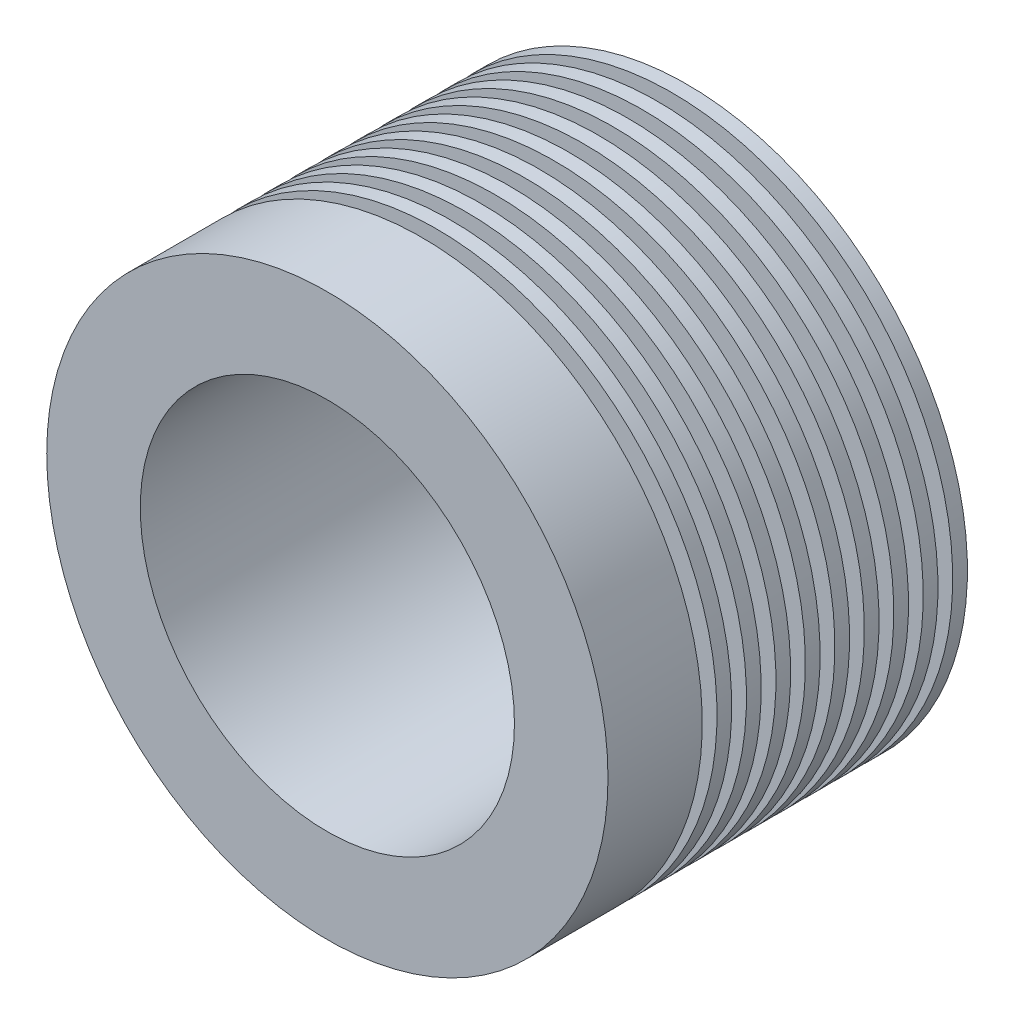
SolidWorks part; units mm, degrees
ref_plane "Plan de face" through (0, 0, 0) normal (0, 0, 1) x (1, 0, 0)
ref_plane "Plan de dessus" through (0, 0, 0) normal (0, 1, 0) x (1, 0, 0)
ref_plane "Plan de droite" through (0, 0, 0) normal (1, 0, 0) x (0, 0, -1)
sketch "Esquisse1" plane through (0, 0, 0) normal (0, 0, 1) x (1, 0, 0)
  circle A0 centre (0, 0) radius 38.1
extrude "Boss.-Extru.1" add sketch "Esquisse1" along normal blind 50.8
sketch "Esquisse2" plane through (0, 0, 0) normal (0, 0, -1) x (-1, 0, 0)
  circle A0 centre (0, 0) radius 31.75
  point P3 (-148.2996, 19.0013)
extrude "Enlèv. mat.-Extru.3" cut sketch "Esquisse2" against normal blind 2 flip side to cut
pattern_linear "Répétition linéaire1" count 10 spacing 4 along (0, 0, 1) of "Enlèv. mat.-Extru.3"
sketch "Esquisse5" plane through (0, 0, 50.8) normal (0, 0, 1) x (1, 0, 0)
  circle A0 centre (0, 0) radius 25.4
extrude "Enlèv. mat.-Extru.5" cut sketch "Esquisse5" against normal blind 44.45
